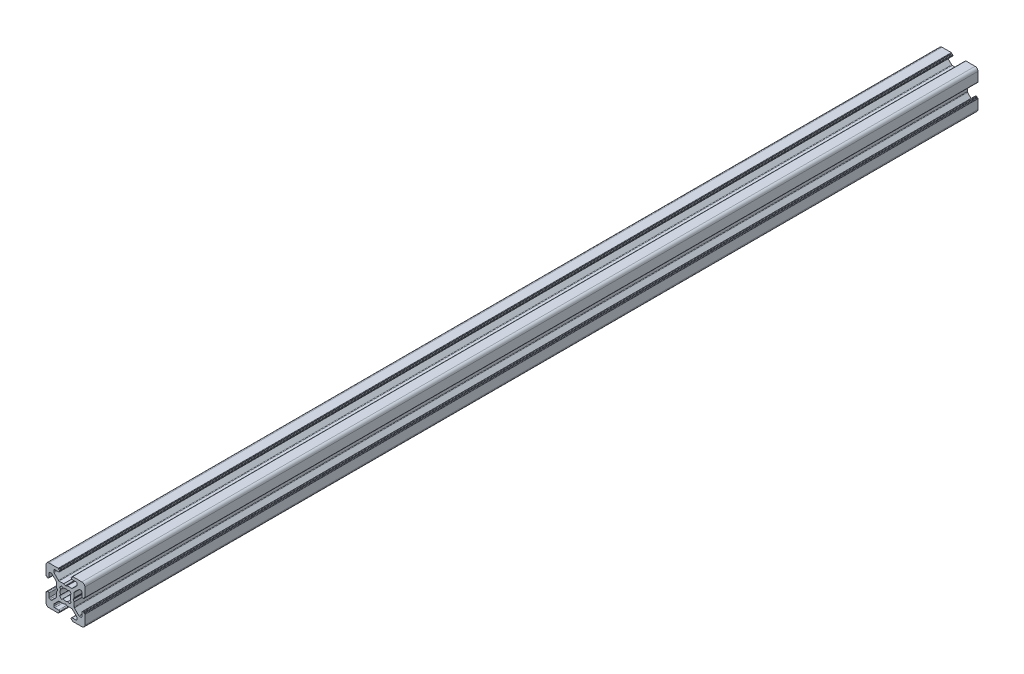
SolidWorks part; units mm, degrees
ref_plane "Ön Düzlem" through (0, 0, 0) normal (0, 0, 1) x (1, 0, 0)
ref_plane "Üst Düzlem" through (0, 0, 0) normal (0, 1, 0) x (1, 0, 0)
ref_plane "Sağ Düzlem" through (0, 0, 0) normal (1, 0, 0) x (0, 0, -1)
sketch "Çizim1" plane through (0, 0, 0) normal (0, 0, 1) x (1, 0, 0)
  line L0 (-2.9922, 1.9099) -> (-2.4453, 1.2582)
  line L1 (-2.4453, -1.2582) -> (-2.9922, -1.9099)
  line L2 (-1.9139, -2.9896) -> (-1.2582, -2.4453)
  line L3 (1.2582, -2.4453) -> (1.9139, -2.9896)
  line L4 (2.9922, -1.9099) -> (2.4453, -1.2582)
  line L5 (2.4453, 1.2582) -> (2.9922, 1.9099)
  line L6 (1.9139, 2.9896) -> (1.2582, 2.4453)
  line L7 (-1.2582, 2.4453) -> (-1.9139, 2.9896)
  line L8 (-3.75, 10) -> (-8.5, 10)
  line L9 (-3.55, 9.7) -> (-3.55, 9.8)
  line L10 (-3.2, 9.5) -> (-3.35, 9.5)
  line L11 (-3, 9) -> (-3, 9.3)
  line L12 (-5.5, 8.5) -> (-3.5, 8.5)
  line L13 (-6, 7.2678) -> (-6, 8)
  line L14 (-3.5858, 4.6464) -> (-5.8536, 6.9142)
  line L15 (-0.9536, 4.5) -> (-3.2322, 4.5)
  line L16 (-0.1, 4.0381) -> (-0.8536, 4.4732)
  line L17 (0.8536, 4.4732) -> (0.1, 4.0381)
  line L18 (3.2322, 4.5) -> (0.9536, 4.5)
  line L19 (5.8536, 6.9142) -> (3.5858, 4.6464)
  line L20 (6, 8) -> (6, 7.2678)
  line L21 (3.5, 8.5) -> (5.5, 8.5)
  line L22 (3, 9.3) -> (3, 9)
  line L23 (3.35, 9.5) -> (3.2, 9.5)
  line L24 (3.55, 9.8) -> (3.55, 9.7)
  line L25 (8.5, 10) -> (3.75, 10)
  line L26 (10, 3.75) -> (10, 8.5)
  line L27 (9.7, 3.55) -> (9.8, 3.55)
  line L28 (9.5, 3.2) -> (9.5, 3.35)
  line L29 (9, 3) -> (9.3, 3)
  line L30 (8.5, 5.5) -> (8.5, 3.5)
  line L31 (7.2678, 6) -> (8, 6)
  line L32 (4.6464, 3.5858) -> (6.9142, 5.8536)
  line L33 (4.5, 0.9536) -> (4.5, 3.2322)
  line L34 (4.0381, 0.1) -> (4.4732, 0.8536)
  line L35 (4.4732, -0.8536) -> (4.0381, -0.1)
  line L36 (4.5, -3.2322) -> (4.5, -0.9536)
  line L37 (6.9142, -5.8536) -> (4.6464, -3.5858)
  line L38 (8, -6) -> (7.2678, -6)
  line L39 (8.5, -3.5) -> (8.5, -5.5)
  line L40 (9.3, -3) -> (9, -3)
  line L41 (9.5, -3.35) -> (9.5, -3.2)
  line L42 (9.8, -3.55) -> (9.7, -3.55)
  line L43 (10, -8.5) -> (10, -3.75)
  line L44 (3.75, -10) -> (8.5, -10)
  line L45 (3.55, -9.7) -> (3.55, -9.8)
  line L46 (3.2, -9.5) -> (3.35, -9.5)
  line L47 (3, -9) -> (3, -9.3)
  line L48 (5.5, -8.5) -> (3.5, -8.5)
  line L49 (6, -7.2678) -> (6, -8)
  line L50 (3.5858, -4.6464) -> (5.8536, -6.9142)
  line L51 (0.9536, -4.5) -> (3.2322, -4.5)
  line L52 (0.1, -4.0381) -> (0.8536, -4.4732)
  line L53 (-0.8536, -4.4732) -> (-0.1, -4.0381)
  line L54 (-3.2322, -4.5) -> (-0.9536, -4.5)
  line L55 (-5.8536, -6.9142) -> (-3.5858, -4.6464)
  line L56 (-6, -8) -> (-6, -7.2678)
  line L57 (-3.5, -8.5) -> (-5.5, -8.5)
  line L58 (-3, -9.3) -> (-3, -9)
  line L59 (-3.35, -9.5) -> (-3.2, -9.5)
  line L60 (-3.55, -9.8) -> (-3.55, -9.7)
  line L61 (-8.5, -10) -> (-3.75, -10)
  line L62 (-10, -3.75) -> (-10, -8.5)
  line L63 (-9.7, -3.55) -> (-9.8, -3.55)
  line L64 (-9.5, -3.2) -> (-9.5, -3.35)
  line L65 (-9, -3) -> (-9.3, -3)
  line L66 (-8.5, -5.5) -> (-8.5, -3.5)
  line L67 (-7.2678, -6) -> (-8, -6)
  line L68 (-4.6464, -3.5858) -> (-6.9142, -5.8536)
  line L69 (-4.5, -0.9536) -> (-4.5, -3.2322)
  line L70 (-4.0381, -0.1) -> (-4.4732, -0.8536)
  line L71 (-4.4732, 0.8536) -> (-4.0381, 0.1)
  line L72 (-4.5, 3.2322) -> (-4.5, 0.9536)
  line L73 (-6.9142, 5.8536) -> (-4.6464, 3.5858)
  line L74 (-8, 6) -> (-7.2678, 6)
  line L75 (-8.5, 3.5) -> (-8.5, 5.5)
  line L76 (-9.3, 3) -> (-9, 3)
  line L77 (-9.5, 3.35) -> (-9.5, 3.2)
  line L78 (-9.8, 3.55) -> (-9.7, 3.55)
  line L79 (-10, 8.5) -> (-10, 3.75)
  arc A0 (-2.4453, 1.2582) -> (-2.4453, -1.2582) centre (0, 0) ccw
  arc A1 (-2.9922, -1.9099) -> (-1.9139, -2.9896) centre (0, 0) ccw
  arc A2 (-1.2582, -2.4453) -> (1.2582, -2.4453) centre (0, 0) ccw
  arc A3 (1.9139, -2.9896) -> (2.9922, -1.9099) centre (0, 0) ccw
  arc A4 (2.4453, -1.2582) -> (2.4453, 1.2582) centre (0, 0) ccw
  arc A5 (2.9922, 1.9099) -> (1.9139, 2.9896) centre (0, 0) ccw
  arc A6 (1.2582, 2.4453) -> (-1.2582, 2.4453) centre (0, 0) ccw
  arc A7 (-1.9139, 2.9896) -> (-2.9922, 1.9099) centre (0, 0) ccw
  arc A8 (-3.55, 9.8) -> (-3.75, 10) centre (-3.75, 9.8) ccw
  arc A9 (-3.55, 9.7) -> (-3.35, 9.5) centre (-3.35, 9.7) ccw
  arc A10 (-3, 9.3) -> (-3.2, 9.5) centre (-3.2, 9.3) ccw
  arc A11 (-3.5, 8.5) -> (-3, 9) centre (-3.5, 9) ccw
  arc A12 (-5.5, 8.5) -> (-6, 8) centre (-5.5, 8) ccw
  arc A13 (-6, 7.2678) -> (-5.8536, 6.9142) centre (-5.5, 7.2678) ccw
  arc A14 (-3.5858, 4.6464) -> (-3.2322, 4.5) centre (-3.2322, 5) ccw
  arc A15 (-0.8536, 4.4732) -> (-0.9536, 4.5) centre (-0.9536, 4.3) ccw
  arc A16 (-0.1, 4.0381) -> (0.1, 4.0381) centre (0, 4.2113) ccw
  arc A17 (0.9536, 4.5) -> (0.8536, 4.4732) centre (0.9536, 4.3) ccw
  arc A18 (3.2322, 4.5) -> (3.5858, 4.6464) centre (3.2322, 5) ccw
  arc A19 (5.8536, 6.9142) -> (6, 7.2678) centre (5.5, 7.2678) ccw
  arc A20 (6, 8) -> (5.5, 8.5) centre (5.5, 8) ccw
  arc A21 (3, 9) -> (3.5, 8.5) centre (3.5, 9) ccw
  arc A22 (3.2, 9.5) -> (3, 9.3) centre (3.2, 9.3) ccw
  arc A23 (3.35, 9.5) -> (3.55, 9.7) centre (3.35, 9.7) ccw
  arc A24 (3.75, 10) -> (3.55, 9.8) centre (3.75, 9.8) ccw
  arc A25 (10, 8.5) -> (8.5, 10) centre (8.5, 8.5) ccw
  arc A26 (9.8, 3.55) -> (10, 3.75) centre (9.8, 3.75) ccw
  arc A27 (9.7, 3.55) -> (9.5, 3.35) centre (9.7, 3.35) ccw
  arc A28 (9.3, 3) -> (9.5, 3.2) centre (9.3, 3.2) ccw
  arc A29 (8.5, 3.5) -> (9, 3) centre (9, 3.5) ccw
  arc A30 (8.5, 5.5) -> (8, 6) centre (8, 5.5) ccw
  arc A31 (7.2678, 6) -> (6.9142, 5.8536) centre (7.2678, 5.5) ccw
  arc A32 (4.6464, 3.5858) -> (4.5, 3.2322) centre (5, 3.2322) ccw
  arc A33 (4.4732, 0.8536) -> (4.5, 0.9536) centre (4.3, 0.9536) ccw
  arc A34 (4.0381, 0.1) -> (4.0381, -0.1) centre (4.2113, 0) ccw
  arc A35 (4.5, -0.9536) -> (4.4732, -0.8536) centre (4.3, -0.9536) ccw
  arc A36 (4.5, -3.2322) -> (4.6464, -3.5858) centre (5, -3.2322) ccw
  arc A37 (6.9142, -5.8536) -> (7.2678, -6) centre (7.2678, -5.5) ccw
  arc A38 (8, -6) -> (8.5, -5.5) centre (8, -5.5) ccw
  arc A39 (9, -3) -> (8.5, -3.5) centre (9, -3.5) ccw
  arc A40 (9.5, -3.2) -> (9.3, -3) centre (9.3, -3.2) ccw
  arc A41 (9.5, -3.35) -> (9.7, -3.55) centre (9.7, -3.35) ccw
  arc A42 (10, -3.75) -> (9.8, -3.55) centre (9.8, -3.75) ccw
  arc A43 (8.5, -10) -> (10, -8.5) centre (8.5, -8.5) ccw
  arc A44 (3.55, -9.8) -> (3.75, -10) centre (3.75, -9.8) ccw
  arc A45 (3.55, -9.7) -> (3.35, -9.5) centre (3.35, -9.7) ccw
  arc A46 (3, -9.3) -> (3.2, -9.5) centre (3.2, -9.3) ccw
  arc A47 (3.5, -8.5) -> (3, -9) centre (3.5, -9) ccw
  arc A48 (5.5, -8.5) -> (6, -8) centre (5.5, -8) ccw
  arc A49 (6, -7.2678) -> (5.8536, -6.9142) centre (5.5, -7.2678) ccw
  arc A50 (3.5858, -4.6464) -> (3.2322, -4.5) centre (3.2322, -5) ccw
  arc A51 (0.8536, -4.4732) -> (0.9536, -4.5) centre (0.9536, -4.3) ccw
  arc A52 (0.1, -4.0381) -> (-0.1, -4.0381) centre (0, -4.2113) ccw
  arc A53 (-0.9536, -4.5) -> (-0.8536, -4.4732) centre (-0.9536, -4.3) ccw
  arc A54 (-3.2322, -4.5) -> (-3.5858, -4.6464) centre (-3.2322, -5) ccw
  arc A55 (-5.8536, -6.9142) -> (-6, -7.2678) centre (-5.5, -7.2678) ccw
  arc A56 (-6, -8) -> (-5.5, -8.5) centre (-5.5, -8) ccw
  arc A57 (-3, -9) -> (-3.5, -8.5) centre (-3.5, -9) ccw
  arc A58 (-3.2, -9.5) -> (-3, -9.3) centre (-3.2, -9.3) ccw
  arc A59 (-3.35, -9.5) -> (-3.55, -9.7) centre (-3.35, -9.7) ccw
  arc A60 (-3.75, -10) -> (-3.55, -9.8) centre (-3.75, -9.8) ccw
  arc A61 (-10, -8.5) -> (-8.5, -10) centre (-8.5, -8.5) ccw
  arc A62 (-9.8, -3.55) -> (-10, -3.75) centre (-9.8, -3.75) ccw
  arc A63 (-9.7, -3.55) -> (-9.5, -3.35) centre (-9.7, -3.35) ccw
  arc A64 (-9.3, -3) -> (-9.5, -3.2) centre (-9.3, -3.2) ccw
  arc A65 (-8.5, -3.5) -> (-9, -3) centre (-9, -3.5) ccw
  arc A66 (-8.5, -5.5) -> (-8, -6) centre (-8, -5.5) ccw
  arc A67 (-7.2678, -6) -> (-6.9142, -5.8536) centre (-7.2678, -5.5) ccw
  arc A68 (-4.6464, -3.5858) -> (-4.5, -3.2322) centre (-5, -3.2322) ccw
  arc A69 (-4.4732, -0.8536) -> (-4.5, -0.9536) centre (-4.3, -0.9536) ccw
  arc A70 (-4.0381, -0.1) -> (-4.0381, 0.1) centre (-4.2113, 0) ccw
  arc A71 (-4.5, 0.9536) -> (-4.4732, 0.8536) centre (-4.3, 0.9536) ccw
  arc A72 (-4.5, 3.2322) -> (-4.6464, 3.5858) centre (-5, 3.2322) ccw
  arc A73 (-6.9142, 5.8536) -> (-7.2678, 6) centre (-7.2678, 5.5) ccw
  arc A74 (-8, 6) -> (-8.5, 5.5) centre (-8, 5.5) ccw
  arc A75 (-9, 3) -> (-8.5, 3.5) centre (-9, 3.5) ccw
  arc A76 (-9.5, 3.2) -> (-9.3, 3) centre (-9.3, 3.2) ccw
  arc A77 (-9.5, 3.35) -> (-9.7, 3.55) centre (-9.7, 3.35) ccw
  arc A78 (-10, 3.75) -> (-9.8, 3.55) centre (-9.8, 3.75) ccw
  arc A79 (-8.5, 10) -> (-10, 8.5) centre (-8.5, 8.5) ccw
extrude "Yükseklik-Ekstrüzyon1" add sketch "Çizim1" along normal mid plane 460
